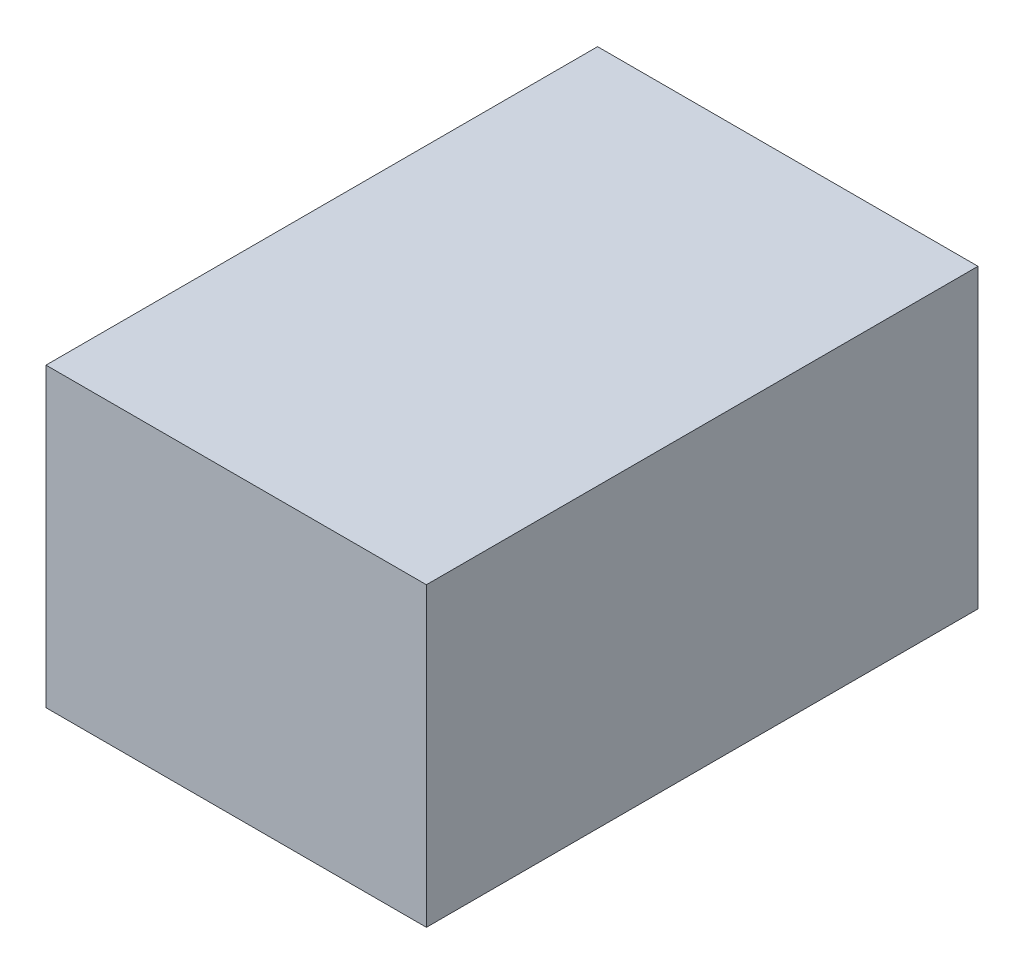
SolidWorks part; units mm, degrees
material "Çam"
ref_plane "Ön Düzlem" through (0, 0, 0) normal (0, 0, 1) x (1, 0, 0)
ref_plane "Üst Düzlem" through (0, 0, 0) normal (0, 1, 0) x (1, 0, 0)
ref_plane "Sağ Düzlem" through (0, 0, 0) normal (1, 0, 0) x (0, 0, -1)
sketch "Çizim1" plane through (0, 0, 0) normal (0, 1, 0) x (1, 0, 0)
  line L1 (-50, -72.5) -> (50, -72.5)
  line L2 (-50, -72.5) -> (-50, 72.5)
  line L3 (-50, 72.5) -> (50, 72.5)
  line L4 (50, -72.5) -> (50, 72.5)
  line L5 (-50, -72.5) -> (50, 72.5) construction
  line L6 (-50, 72.5) -> (50, -72.5) construction
  point P0 (0, 0)
  dimension "D1" = 145
  dimension "D2" = 100
extrude "Yükseklik-Ekstrüzyon1" add sketch "Çizim1" along normal blind 78
